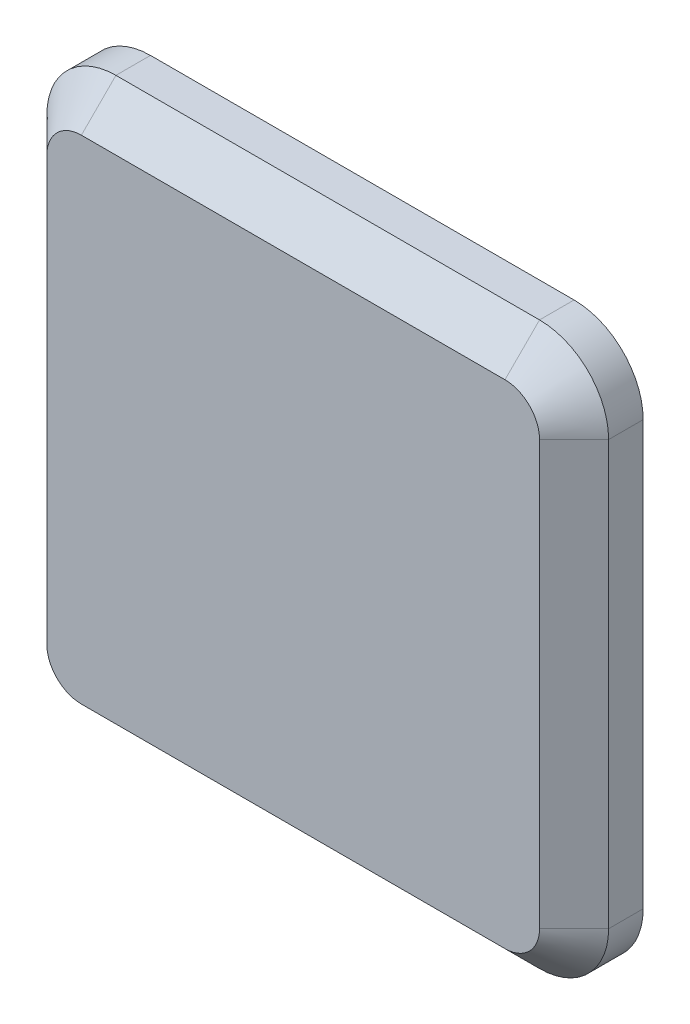
SolidWorks part; units mm, degrees
ref_plane "Front Plane" through (0, 0, 0) normal (0, 0, 1) x (1, 0, 0)
ref_plane "Top Plane" through (0, 0, 0) normal (0, 1, 0) x (1, 0, 0)
ref_plane "Right Plane" through (0, 0, 0) normal (1, 0, 0) x (0, 0, -1)
sketch "Sketch1" plane through (0, 0, 0) normal (0, 0, 1) x (1, 0, 0)
  line L1 (16.2635, -16.2635) -> (-16.2635, -16.2635)
  line L2 (16.2635, -16.2635) -> (16.2635, 16.2635)
  line L3 (16.2635, 16.2635) -> (-16.2635, 16.2635)
  line L4 (-16.2635, -16.2635) -> (-16.2635, 16.2635)
  line L5 (16.2635, -16.2635) -> (-16.2635, 16.2635) construction
  line L6 (16.2635, 16.2635) -> (-16.2635, -16.2635) construction
  point P0 (0, 0)
  dimension "D1" = 46
extrude "Boss-Extrude1" add sketch "Sketch1" along normal blind 4
fillet "Fillet1" radius 4 4 edges at (-16.2635, -16.2635, 2) (16.2635, -16.2635, 2) (16.2635, 16.2635, 2) (-16.2635, 16.2635, 2)
chamfer "Chamfer1" distance 2 angle 45 8 edges at (0, -16.2635, 4) (15.0919, -15.0919, 4) (-15.0919, -15.0919, 4) (16.2635, 0, 4) (-16.2635, 0, 4) (15.0919, 15.0919, 4) (-15.0919, 15.0919, 4) (0, 16.2635, 4)
sketch "Sketch2" plane through (0, 0, 4) normal (0, 0, 1) x (1, 0, 0)
  line L0 (0, 0) -> (14.2635, 0) construction
  line L1 (14.2635, -12.2635) -> (14.2635, 12.2635) construction
  line L2 (14.2635, 0) -> (-14.2635, 0) construction
  line L3 (-14.2635, 12.2635) -> (-14.2635, -12.2635) construction
  line L4 (-14.2635, 0) -> (0, 0) construction
  line L5 (0, 0) -> (0, -14.2635) construction
  line L6 (-12.2635, -14.2635) -> (12.2635, -14.2635) construction
  line L7 (0, -14.2635) -> (0, 14.2635) construction
  line L8 (12.2635, 14.2635) -> (-12.2635, 14.2635) construction
